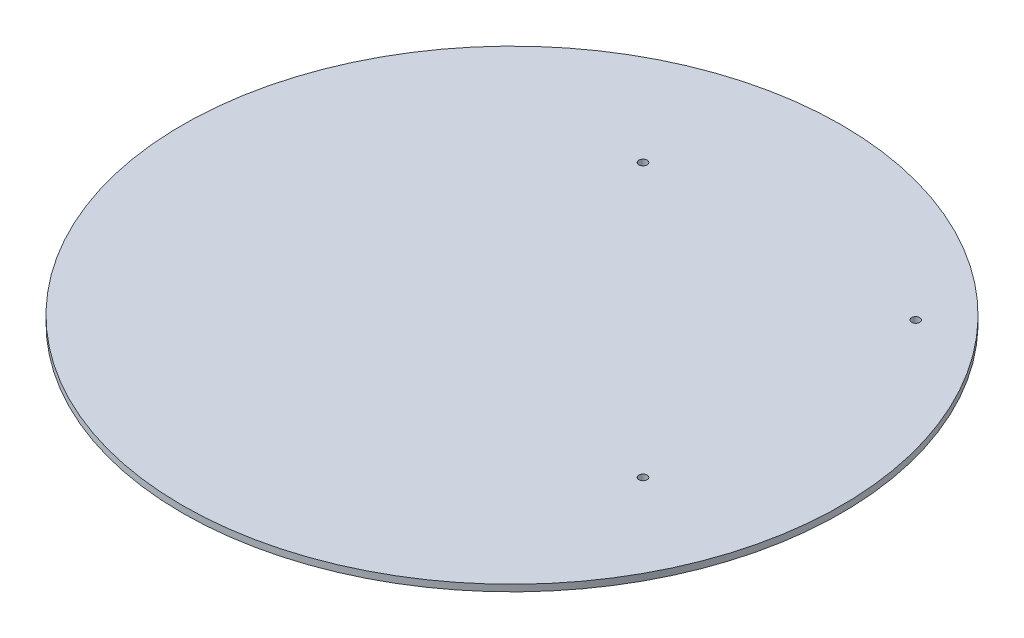
SolidWorks part; units mm, degrees
material "Acrylic (Medium-high impact)"
ref_plane "Front Plane" through (0, 0, 0) normal (0, 0, 1) x (1, 0, 0)
ref_plane "Top Plane" through (0, 0, 0) normal (0, 1, 0) x (1, 0, 0)
ref_plane "Right Plane" through (0, 0, 0) normal (1, 0, 0) x (0, 0, -1)
sketch "Sketch1" plane through (0, 0, 0) normal (0, 1, 0) x (1, 0, 0)
  circle A0 centre (0, 0) radius 200
  circle A1 centre (125, 120) radius 2.5
  circle A2 centre (-40.5, 120) radius 2.5
  circle A3 centre (125, -45.5) radius 2.5
  dimension "D1" = 165.5
  dimension "D3" = 5
  dimension "D4" = 400
  dimension "D5" = 125
  dimension "D2" = 165.5
  dimension "D6" = 120
extrude "Boss-Extrude1" add sketch "Sketch1" along normal blind 4 contours A0 | A2 | A1 | A3
